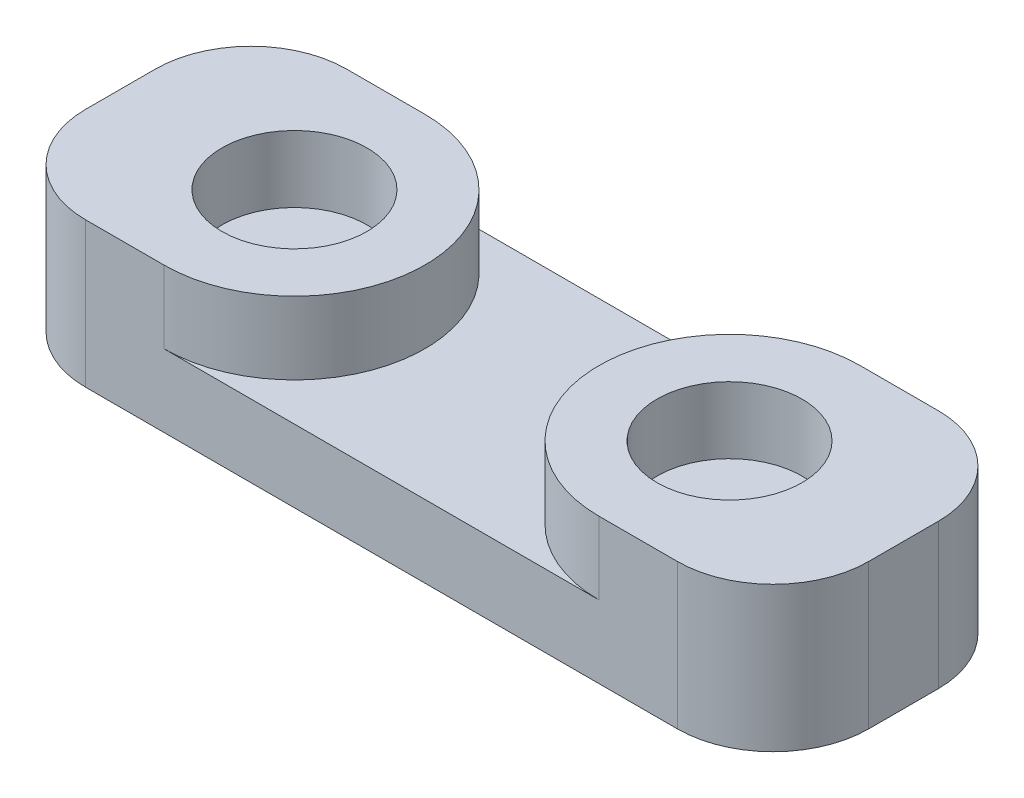
SolidWorks part; units mm, degrees
ref_plane "Front Plane" through (0, 0, 0) normal (0, 0, 1) x (1, 0, 0)
ref_plane "Top Plane" through (0, 0, 0) normal (0, 1, 0) x (1, 0, 0)
ref_plane "Right Plane" through (0, 0, 0) normal (1, 0, 0) x (0, 0, -1)
sketch "Sketch1" plane through (0, 0, 0) normal (0, 1, 0) x (1, 0, 0)
  line L1 (-13.5, 4.5) -> (13.5, 4.5)
  line L2 (-13.5, 4.5) -> (-13.5, -4.5)
  line L3 (-13.5, -4.5) -> (13.5, -4.5)
  line L4 (13.5, 4.5) -> (13.5, -4.5)
  line L5 (-13.5, 4.5) -> (13.5, -4.5) construction
  line L6 (-13.5, -4.5) -> (13.5, 4.5) construction
  point P0 (0, 0)
  dimension "D1" = 27
  dimension "D2" = 9
extrude "Boss-Extrude1" add sketch "Sketch1" along normal blind 5
fillet "Fillet1" radius 3.3 4 edges at (-13.5, 2.5, -4.5) (-13.5, 2.5, 4.5) (13.5, 2.5, 4.5) (13.5, 2.5, -4.5)
sketch "Sketch2" plane through (0, 5, 0) normal (0, 1, 0) x (1, 0, 0)
  circle A0 centre (-7.5, 0) radius 2.5
  circle A1 centre (7.5, 0) radius 2.5
  point P4 (0, 0)
  point P6 (0, 0)
  dimension "D1" = 5
  dimension "D2" = 15
  dimension "D3" = 7.5
extrude "Cut-Extrude1" cut sketch "Sketch2" against normal blind 2.3
sketch "Sketch4" plane through (0, 5, 0) normal (0, 1, 0) x (1, 0, 0)
  line L0 (-10.2, -4.5) -> (10.2, -4.5) construction
  line L1 (10.2, 4.5) -> (-10.2, 4.5) construction
  line L2 (-10.2, -4.5) -> (10.2, -4.5)
  line L3 (10.2, 4.5) -> (-10.2, 4.5)
  circle A0 centre (-7.5, 0) radius 2.5 construction
  circle A1 centre (-7.5, 0) radius 2.5
  circle A2 centre (7.5, 0) radius 2.5 construction
  circle A3 centre (7.5, 0) radius 2.5
  circle A4 centre (-7.5, 0) radius 4.5
  circle A5 centre (7.5, 0) radius 4.5
extrude "Cut-Extrude4" cut sketch "Sketch4" against normal blind 2.5 contours A5 L3 A4 L2
